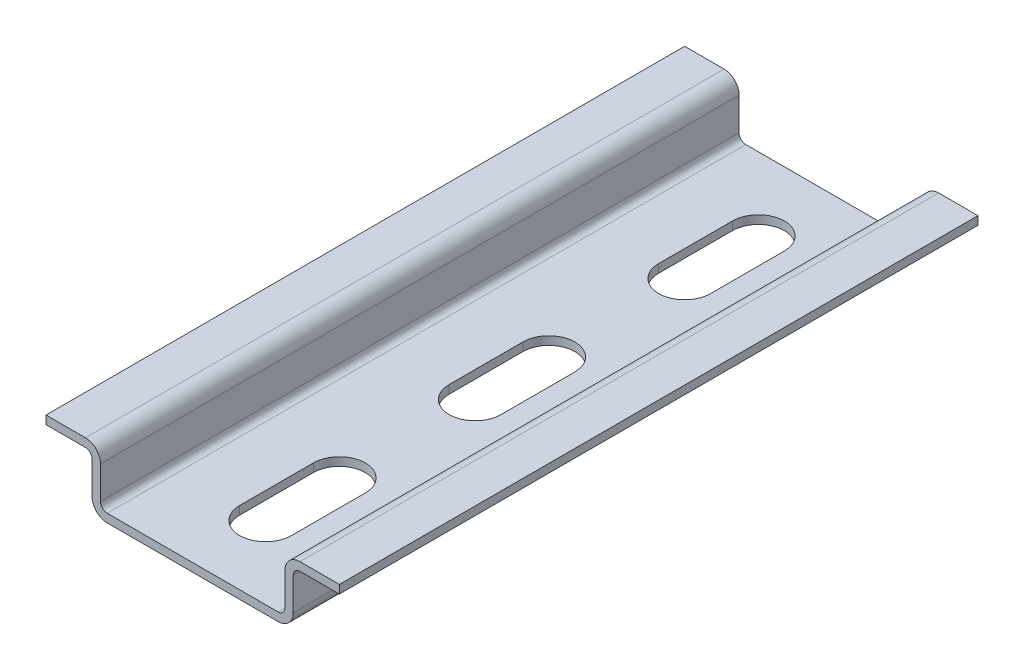
SolidWorks part; units mm, degrees
ref_plane "Plane1" through (0, 0, 0) normal (0, 0, 1) x (1, 0, 0)
ref_plane "Plane2" through (0, 0, 0) normal (0, 1, 0) x (1, 0, 0)
ref_plane "Plane3" through (0, 0, 0) normal (1, 0, 0) x (0, 0, -1)
sketch "Sketch1" plane through (0, 0, 0) normal (0, 0, 1) x (1, 0, 0)
  line L0 (0, 44.8074) -> (0, -51.5339) construction
  line L1 (-12, 0) -> (12, 0)
  line L2 (12, 0) -> (12, 6.5)
  line L3 (12, 6.5) -> (17.5, 6.5)
  line L4 (-12, 6.5) -> (-17.5, 6.5)
  line L5 (-12, 0) -> (-12, 6.5)
  point P10 (0, 0)
  dimension "D1" = 24
  dimension "D2" = 6.5
  dimension "D3" = 35
extrude "Base-Extrude-Thin" add sketch "Sketch1" against normal mid plane 508 thin thin type one direction wall 1
fillet "Fillet1" radius 0.8 4 edges at (-11, 1, 0) (11, 1, 0) (12, 6.5, 0) (-12, 6.5, 0)
fillet "Fillet2" radius 1.8 4 edges at (-11, 7.5, 0) (11, 7.5, 0) (12, 0, 0) (-12, 0, 0)
sketch "Sketch2" plane through (0, 1, 0) normal (0, 1, 0) x (-1, 0, 0)
  line L0 (27.3429, 0) -> (-19.5279, 0) construction
  line L1 (3.1, 4.4) -> (3.1, -4.4)
  line L2 (-3.1, -4.4) -> (-3.1, 4.4)
  arc A0 (3.1, -4.4) -> (-3.1, -4.4) centre (0, -4.4) cw
  arc A1 (3.1, 4.4) -> (-3.1, 4.4) centre (0, 4.4) ccw
  point P8 (3.1, 0)
  point P11 (-3.1, 0)
  dimension "D1" = 6.2
  dimension "D2" = 15
extrude "Cut-Extrude1" cut sketch "Sketch2" against normal through all
pattern_linear "LPattern1" count 10 spacing 25 along (0, 0, -1) of "Cut-Extrude1"
mirror "Mirror1" about plane through (0, 0, 0) normal (0, 0, 1) of "LPattern1"
sketch "Sketch3" plane through (0, 7.5, 0) normal (0, 1, 0) x (-1, 0, 0)
  line L0 (-51.2266, 38.1) -> (48.228, 38.1)
  line L1 (-51.2266, -38.1) -> (48.228, -38.1)
  line L2 (-32.1488, 0) -> (32.2777, 0) construction
  line L3 (-51.2266, 38.1) -> (-51.2266, -38.1)
  line L4 (48.228, 38.1) -> (48.228, -38.1)
  dimension "D1" = 76.2
extrude "Cut-Extrude2 (3\")" cut sketch "Sketch3" against normal through all flip side to cut
